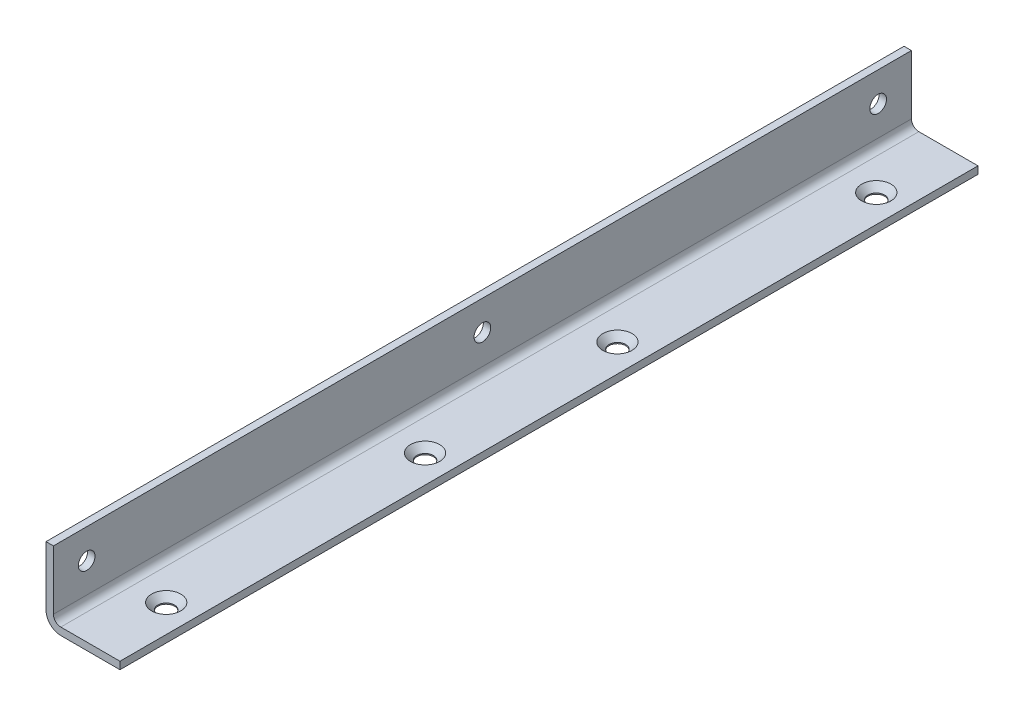
SolidWorks part; units mm, degrees
ref_plane "Спереди" through (0, 0, 0) normal (0, 0, 1) x (1, 0, 0)
ref_plane "Сверху" through (0, 0, 0) normal (0, 1, 0) x (1, 0, 0)
ref_plane "Справа" through (0, 0, 0) normal (1, 0, 0) x (0, 0, -1)
sketch "Эскиз1" plane through (0, 0, 0) normal (0, 0, 1) x (1, 0, 0)
  line L1 (0, 0) -> (20, 0)
  line L2 (0, 0) -> (0, 20)
  line L3 (0, 20) -> (2, 20)
  line L4 (20, 0) -> (20, 2)
  line L5 (4, 2) -> (20, 2)
  line L6 (2, 4) -> (2, 20)
  arc A0 (4, 2) -> (2, 4) centre (4, 4) cw
  dimension "D5" = 2
  dimension "D1" = 20
  dimension "D2" = 20
  dimension "D3" = 2
  dimension "D4" = 2
extrude "Вытянуть1" add sketch "Эскиз1" along normal blind 232
sketch "Эскиз2" plane through (2, 0, 0) normal (1, 0, 0) x (0, 0, -1)
  line L0 (-116, 12) -> (-116, 74.4355) construction
  line L2 (-232, 4) -> (-232, 20) construction
  line L3 (-280.1291, 12) -> (26.6955, 12) construction
  line L4 (-232, 20) -> (0, 20) construction
  line L5 (0, 4) -> (0, 20) construction
  circle A0 centre (-223, 12) radius 2.25
  circle A1 centre (-9, 12) radius 2.25
  circle A2 centre (-116, 12) radius 2.25
  dimension "D2" = 4.5
  dimension "D5" = 107
  dimension "D4" = 214
  dimension "D1" = 8
extrude "Вырез-Вытянуть1" cut sketch "Эскиз2" against normal blind 10
sketch "Эскиз3" plane through (0, 2, 0) normal (0, 1, 0) x (1, 0, 0)
  line L0 (-101.7059, -116) -> (103.8615, -116) construction
  line L1 (20, 0) -> (4, 0) construction
  line L2 (20, -232) -> (4, -232) construction
  line L4 (12.5, -212) -> (12.5, -20) construction
  line L5 (20, -232) -> (20, 0) construction
  circle A1 centre (12.5, -212) radius 2.25
  circle A2 centre (12.5, -142) radius 2.25
  circle A5 centre (12.5, -20) radius 2.25
  circle A8 centre (12.5, -90) radius 2.25
  dimension "D1" = 70
  dimension "D2" = 4.5
  dimension "D3" = 7.5
  dimension "D4" = 20
extrude "Вырез-Вытянуть2" cut sketch "Эскиз3" against normal blind 10
chamfer "Фаска1" distance 1.7 angle 45 4 edges at (12.5, 2, 17.75) (12.5, 2, 92.25) (12.5, 2, 139.75) (12.5, 2, 214.25)
fillet "Скругление1" radius 4 1 edges at (0, 0, 116)
